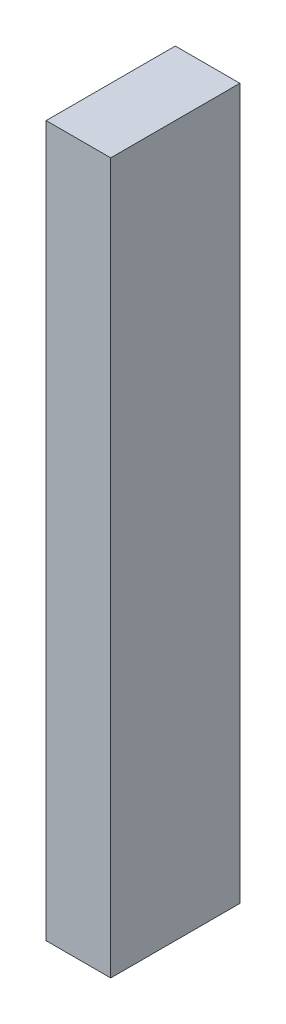
SolidWorks part; units mm, degrees
material "Teak"
ref_plane "Front Plane" through (0, 0, 0) normal (0, 0, 1) x (1, 0, 0)
ref_plane "Top Plane" through (0, 0, 0) normal (0, 1, 0) x (1, 0, 0)
ref_plane "Right Plane" through (0, 0, 0) normal (1, 0, 0) x (0, 0, -1)
sketch "Sketch1" plane through (0, 0, 0) normal (0, 1, 0) x (1, 0, 0)
  line L1 (0, 0) -> (50.8, 0)
  line L2 (0, 0) -> (0, 101.6)
  line L3 (0, 101.6) -> (50.8, 101.6)
  line L4 (50.8, 0) -> (50.8, 101.6)
  dimension "D1" = 101.6
  dimension "D2" = 50.8
extrude "Boss-Extrude1" add sketch "Sketch1" along normal blind 558.8
